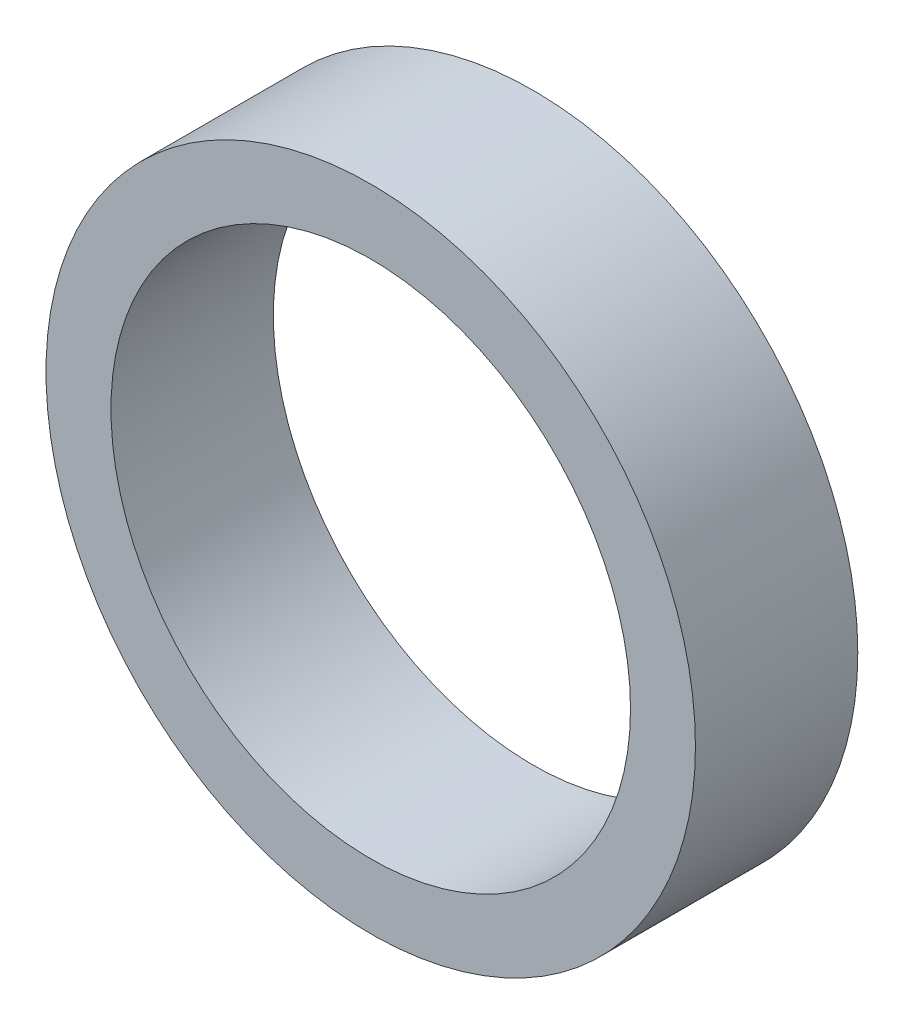
SolidWorks part; units mm, degrees
ref_plane "前视基准面" through (0, 0, 0) normal (0, 0, 1) x (1, 0, 0)
ref_plane "上视基准面" through (0, 0, 0) normal (0, 1, 0) x (1, 0, 0)
ref_plane "右视基准面" through (0, 0, 0) normal (1, 0, 0) x (0, 0, -1)
sketch "草图1" plane through (0, 0, 0) normal (0, 0, 1) x (1, 0, 0)
  circle A0 centre (0, 0) radius 2
  circle A1 centre (0, 0) radius 1.6
  dimension "D1" = 3.2
  dimension "D2" = 0.4
extrude "凸台-拉伸1" add sketch "草图1" along normal blind 1
